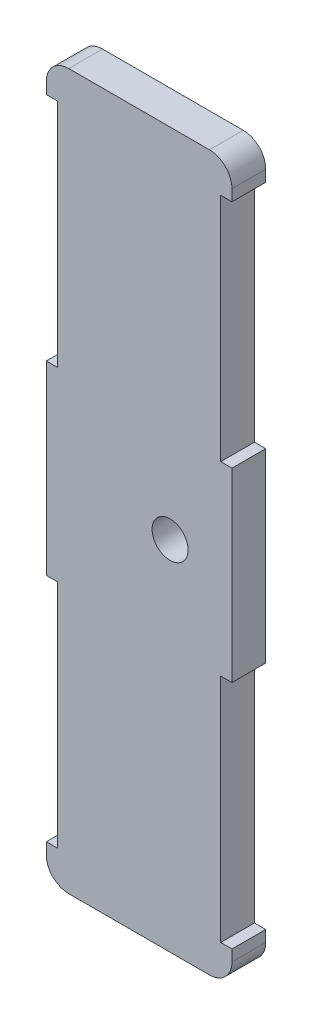
SolidWorks part; units mm, degrees
ref_plane "Front Plane" through (0, 0, 0) normal (0, 0, 1) x (1, 0, 0)
ref_plane "Top Plane" through (0, 0, 0) normal (0, 1, 0) x (1, 0, 0)
ref_plane "Right Plane" through (0, 0, 0) normal (1, 0, 0) x (0, 0, -1)
sketch "Sketch1" plane through (0, 0, 0) normal (0, 0, 1) x (1, 0, 0)
  line L0 (-45.5, 28.75) -> (-45.5, 8.25)
  line L1 (-45.5, 8.25) -> (-44.5, 8.25)
  line L2 (-44.5, 8.25) -> (-44.5, -8.25)
  line L3 (-44.5, -8.25) -> (-45.5, -8.25)
  line L4 (-45.5, -8.25) -> (-45.5, -28.75)
  line L5 (-44.5, -31.75) -> (-61, -31.75)
  line L6 (-61, -31.75) -> (-61, -28.75)
  line L7 (-61, 31.75) -> (-44.5, 31.75)
  line L8 (-61, 0) -> (-50, 0) construction
  line L9 (-50, 0) -> (-45.5, 0) construction
  line L10 (-45.5, -8.25) -> (-45.5, 8.25) construction
  line L11 (-45.5, 28.75) -> (-44.5, 28.75)
  line L12 (-44.5, 28.75) -> (-44.5, 31.75)
  line L13 (-45.5, -28.75) -> (-44.5, -28.75)
  line L14 (-44.5, -28.75) -> (-44.5, -31.75)
  line L15 (-61, 28.75) -> (-60, 28.75)
  line L16 (-60, 28.75) -> (-60, 8.25)
  line L17 (-60, 8.25) -> (-61, 8.25)
  line L18 (-61, -8.25) -> (-60, -8.25)
  line L19 (-60, -8.25) -> (-60, -28.75)
  line L20 (-60, -28.75) -> (-61, -28.75)
  line L21 (-61, -8.25) -> (-61, 8.25)
  line L22 (-61, 28.75) -> (-61, 31.75)
  circle A0 centre (-50, 0) radius 1.6
  dimension "D5" = 3.2
  dimension "D1" = 4.5
  dimension "D2" = 1
  dimension "D3" = 16.5
  dimension "D4" = 10
  dimension "D6" = 1
  dimension "D7" = 57.5
  dimension "D8" = 50
  dimension "D9" = 3
  dimension "D10" = 3
extrude "Boss-Extrude1" add sketch "Sketch1" along normal blind 3
fillet "Fillet1" radius 2 4 edges at (-61, 31.75, 1.5) (-44.5, 31.75, 1.5) (-44.5, -31.75, 1.5) (-61, -31.75, 1.5)
